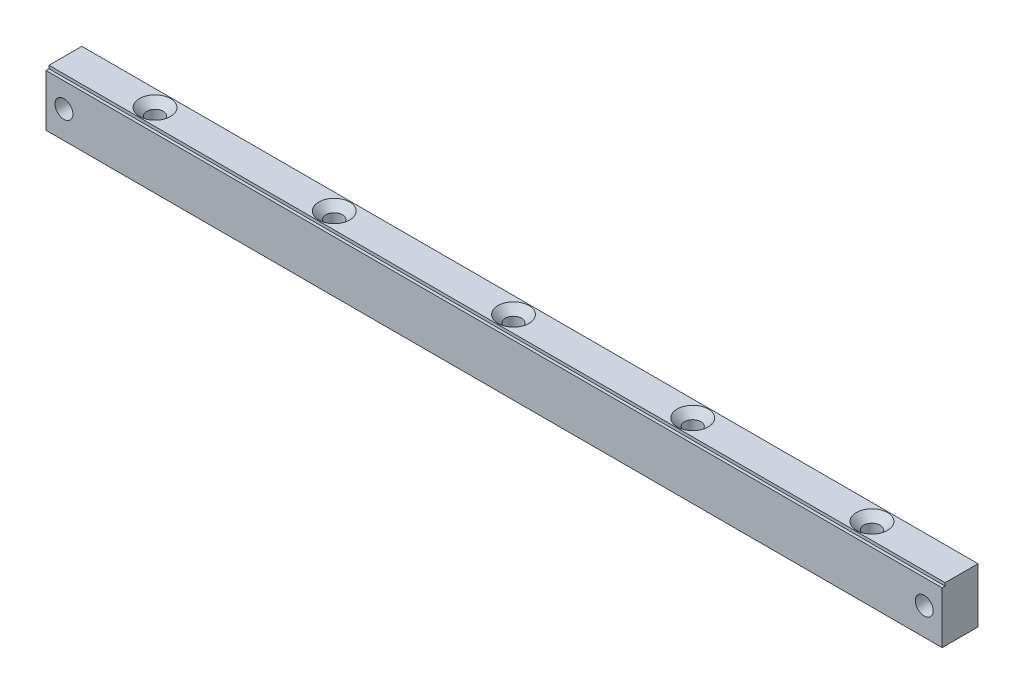
SolidWorks part; units mm, degrees
material "3.1355 (EN-AW 2024)"
ref_plane "Спереди" through (0, 0, 0) normal (0, 0, 1) x (1, 0, 0)
ref_plane "Сверху" through (0, 0, 0) normal (0, 1, 0) x (1, 0, 0)
ref_plane "Справа" through (0, 0, 0) normal (1, 0, 0) x (0, 0, -1)
sketch "Эскиз1" plane through (0, 0, 0) normal (0, 1, 0) x (1, 0, 0)
  line L1 (-150, 12) -> (150, 12)
  line L2 (-150, 12) -> (-150, 0)
  line L3 (-150, 0) -> (150, 0)
  line L4 (150, 12) -> (150, 0)
  point P4 (0, 0)
  dimension "D1" = 300
  dimension "D2" = 12
extrude "База" add sketch "Эскиз1" along normal blind 18.35
sketch "Эскиз2" plane through (0, 18.35, 0) normal (0, 1, 0) x (1, 0, 0)
  line L0 (150, 0) -> (150, 12) construction
  line L1 (-150, 0) -> (150, 0)
  line L2 (-150, 0) -> (-150, 1)
  line L3 (-150, 1) -> (150, 1)
  line L4 (150, 0) -> (150, 1)
  dimension "D1" = 1
extrude "Вырез-Вытянуть1" cut sketch "Эскиз2" against normal blind 1
hole_wizard "Крепление-M4" positions "Эскиз3" profile "Эскиз4" countersink size "M5" standard "DIN" end condition through all
sketch "Эскиз3" plane through (0, 18.35, 0) normal (0, -1, 0) x (-1, 0, 0)
  line L0 (0, 6.5) -> (0, 1) construction
  line L3 (-150, 1) -> (150, 1) construction
  line L4 (0, 6.5) -> (0, 12) construction
  line L5 (-150, 12) -> (150, 12) construction
  point P0 (0, 6.5)
sketch "Эскиз4" plane through (0, 18.35, -6.5) normal (1, 0, 0) x (0, 0, 1)
  line L0 (0, 0) -> (0, 18.35)
  line L1 (0, 18.35) -> (2.75, 18.35)
  line L2 (2.75, 18.35) -> (2.75, 2.45)
  line L3 (2.75, 2.45) -> (5.2, 0)
  line L5 (5.2, 0) -> (0, 0)
  line L6 (-2.75, 2.45) -> (-5.2, 0) construction
  line L11 (0, -6.35) -> (0, 107.95) construction
  dimension "Диаметр сквозного отверстия" = 5.5
  dimension "Глубина сквозного отверстия" = 18.35
  dimension "Диаметр передней зенковки" = 10.4
  dimension "Угол передней зенковки" = 90
pattern_linear "Линейный массив1" count 3 spacing 60 along (-1, 0, 0) count 3 spacing 60 along (1, 0, 0) of "Крепление-M4"
sketch "Эскиз5" plane through (0, 0, -12) normal (0, 0, 1) x (1, 0, 0)
  line L0 (-150, 17.35) -> (-150, 0) construction
  line L1 (-150, 18.35) -> (-150, 0) construction
  line L2 (144, 9.175) -> (150, 9.175) construction
  line L3 (-144, 9.175) -> (-150, 9.175) construction
  line L6 (150, 17.35) -> (150, 0) construction
  circle A0 centre (-144, 9.175) radius 3
  circle A1 centre (144, 9.175) radius 3
  point P12 (-150, 9.175)
  dimension "D1" = 6
  dimension "D2" = 6
extrude "Валы-6мм" cut sketch "Эскиз5" along normal through all
